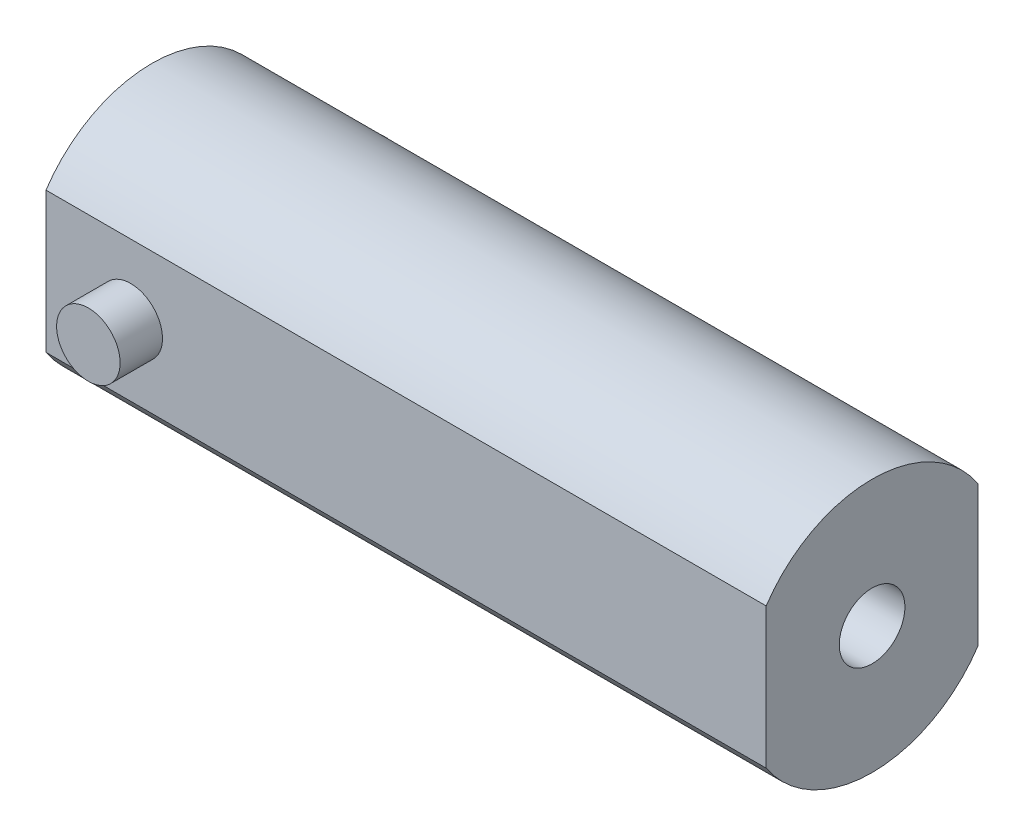
SolidWorks part; units mm, degrees
ref_plane "Front Plane" through (0, 0, 0) normal (0, 0, 1) x (1, 0, 0)
ref_plane "Top Plane" through (0, 0, 0) normal (0, 1, 0) x (1, 0, 0)
ref_plane "Right Plane" through (0, 0, 0) normal (1, 0, 0) x (0, 0, -1)
sketch "Sketch1" plane through (0, 0, 0) normal (1, 0, 0) x (0, 0, -1)
  line L0 (0, 30) -> (0, -30) construction
  line L1 (-25, 16.5831) -> (-25, -16.5831)
  line L2 (25, 16.5831) -> (25, -16.5831)
  line L3 (-25, 30) -> (-25, -30) construction
  line L4 (25, 30) -> (25, -30) construction
  arc A0 (25, 16.5831) -> (-25, 16.5831) centre (0, 0) ccw
  arc A1 (-25, -16.5831) -> (25, -16.5831) centre (0, 0) ccw
  dimension "D1" = 60
  dimension "D2" = 25
  dimension "D3" = 25
extrude "Boss-Extrude1" add sketch "Sketch1" along normal blind 170
sketch "Sketch3" plane through (0, 0, 25) normal (0, 0, 1) x (1, 0, 0)
  circle A0 centre (20, 0) radius 7.5
  dimension "D1" = 15
  dimension "D2" = 20
extrude "Boss-Extrude2" add sketch "Sketch3" along normal blind 10
mirror "Mirror1" about plane through (0, 0, 0) normal (0, 0, 1) of "Boss-Extrude2"
sketch "Sketch4" plane through (170, 0, 0) normal (1, 0, 0) x (0, 0, -1)
  circle A0 centre (0, 0) radius 7.75
  dimension "D1" = 15.5
extrude "Cut-Extrude1" cut sketch "Sketch4" against normal blind 17
